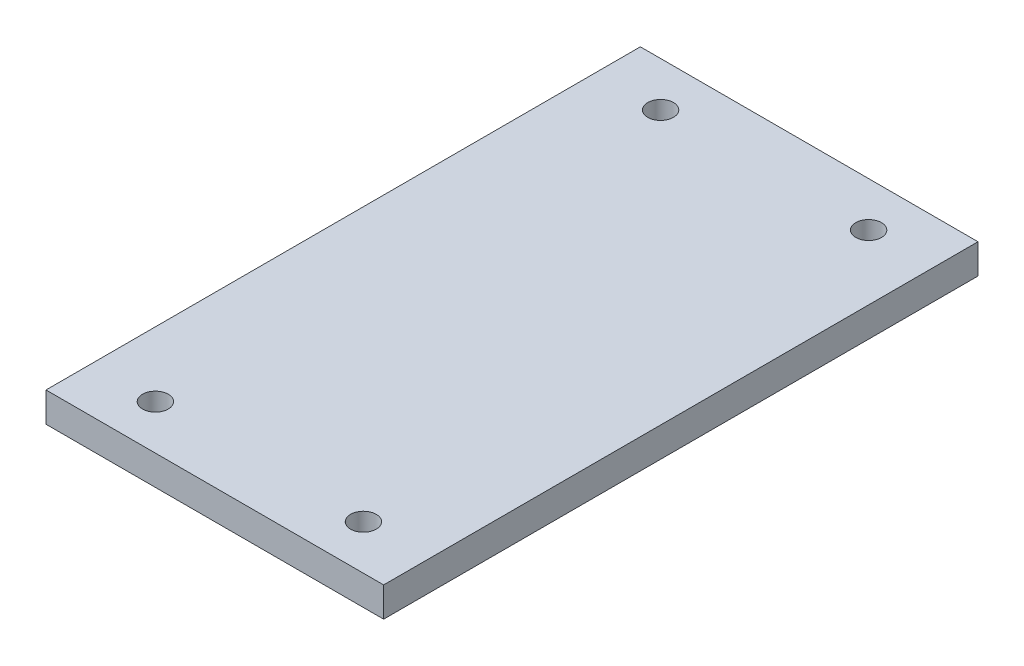
SolidWorks part; units mm, degrees
ref_plane "Front Plane" through (0, 0, 0) normal (0, 0, 1) x (1, 0, 0)
ref_plane "Top Plane" through (0, 0, 0) normal (0, 1, 0) x (1, 0, 0)
ref_plane "Right Plane" through (0, 0, 0) normal (1, 0, 0) x (0, 0, -1)
sketch "Sketch2" plane through (0, 0, 0) normal (0, 1, 0) x (1, 0, 0)
  line L1 (-36.0719, -63.5) -> (36.0719, -63.5)
  line L2 (-36.0719, -63.5) -> (-36.0719, 63.5)
  line L3 (-36.0719, 63.5) -> (36.0719, 63.5)
  line L4 (36.0719, -63.5) -> (36.0719, 63.5)
  line L5 (-36.0719, -63.5) -> (36.0719, 63.5) construction
  line L6 (-36.0719, 63.5) -> (36.0719, -63.5) construction
  point P0 (0, 0)
  dimension "D1" = 127
  dimension "D2" = 72.1437
extrude "Boss-Extrude1" add sketch "Sketch2" along normal blind 6.35
sketch "Sketch3" plane through (0, 6.35, 0) normal (0, 1, 0) x (1, 0, 0)
  line L0 (0, -63.5) -> (0, 63.5) construction
  line L1 (-36.0719, -63.5) -> (36.0719, -63.5) construction
  line L2 (36.0719, 63.5) -> (-36.0719, 63.5) construction
  line L8 (-36.0719, 53.975) -> (36.0719, 53.975) construction
  line L10 (-36.0719, 63.5) -> (-36.0719, -63.5) construction
  line L11 (36.0719, -63.5) -> (36.0719, 63.5) construction
  line L12 (-3.4925, 0) -> (3.4925, 0) construction
  circle A4 centre (-22.225, 53.975) radius 2.75
  circle A5 centre (22.225, 53.975) radius 2.75
  circle A6 centre (22.225, -53.975) radius 2.75
  circle A7 centre (-22.225, -53.975) radius 2.75
  point P6 (0, 57.5747)
  dimension "D3" = 5.5
  dimension "D1" = 9.525
  dimension "D2" = 44.45
extrude "Cut-Extrude1" cut sketch "Sketch3" against normal blind 6.35
